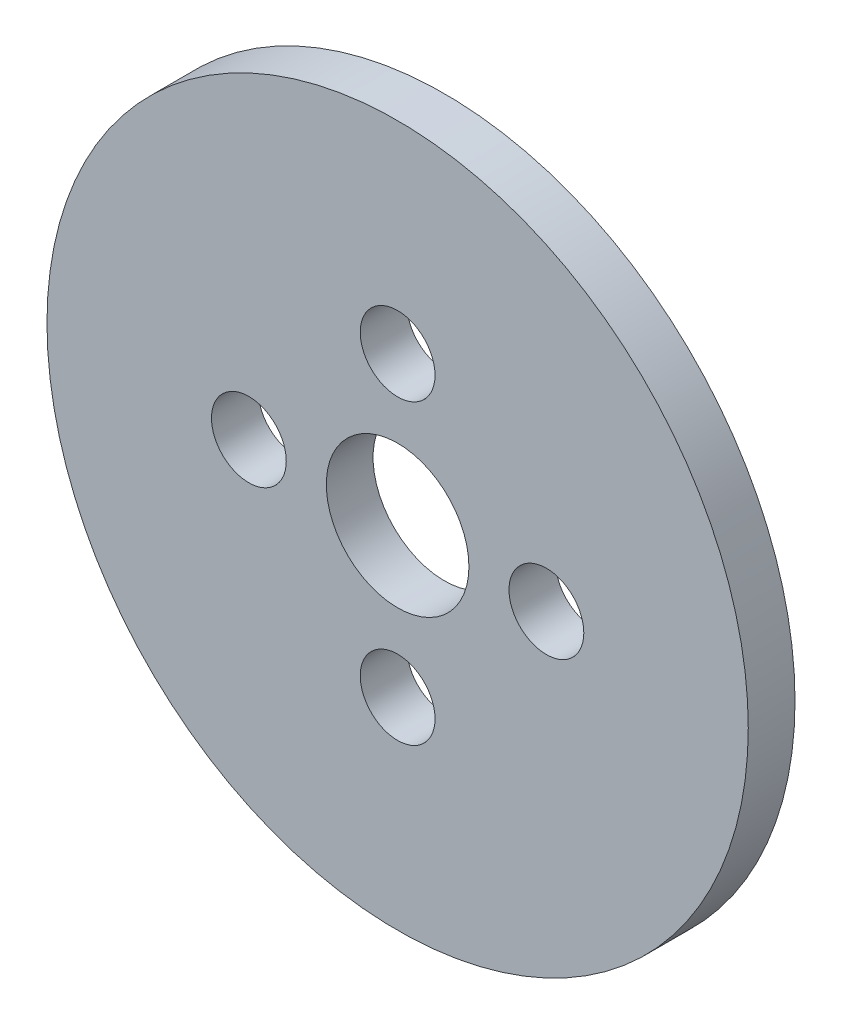
SolidWorks part; units mm, degrees
ref_plane "正面" through (0, 0, 0) normal (0, 0, 1) x (1, 0, 0)
ref_plane "平面" through (0, 0, 0) normal (0, 1, 0) x (1, 0, 0)
ref_plane "右側面" through (0, 0, 0) normal (1, 0, 0) x (0, 0, -1)
sketch "ｽｹｯﾁ1" plane through (0, 0, 0) normal (0, 0, 1) x (1, 0, 0)
  line L1 (6.364, 0) -> (0, 6.364) construction
  line L2 (0, 6.364) -> (-6.364, 0) construction
  line L3 (-6.364, 0) -> (0, -6.364) construction
  line L4 (0, -6.364) -> (6.364, 0) construction
  circle A0 centre (0, 0) radius 15
  circle A1 centre (0, 0) radius 4.5 construction
  circle A2 centre (0, 6.364) radius 1.6
  circle A3 centre (6.364, 0) radius 1.6
  circle A4 centre (-6.364, 0) radius 1.6
  circle A5 centre (0, -6.364) radius 1.6
  circle A6 centre (0, 0) radius 3.05
  dimension "D1" = 30
  dimension "D3" = 3.2
  dimension "D4" = 3.2
  dimension "D5" = 3.2
  dimension "D6" = 3.2
  dimension "D7" = 6.1
  dimension "D2" = 9
extrude "ﾎﾞｽ - 押し出し1" add sketch "ｽｹｯﾁ1" along normal blind 2
